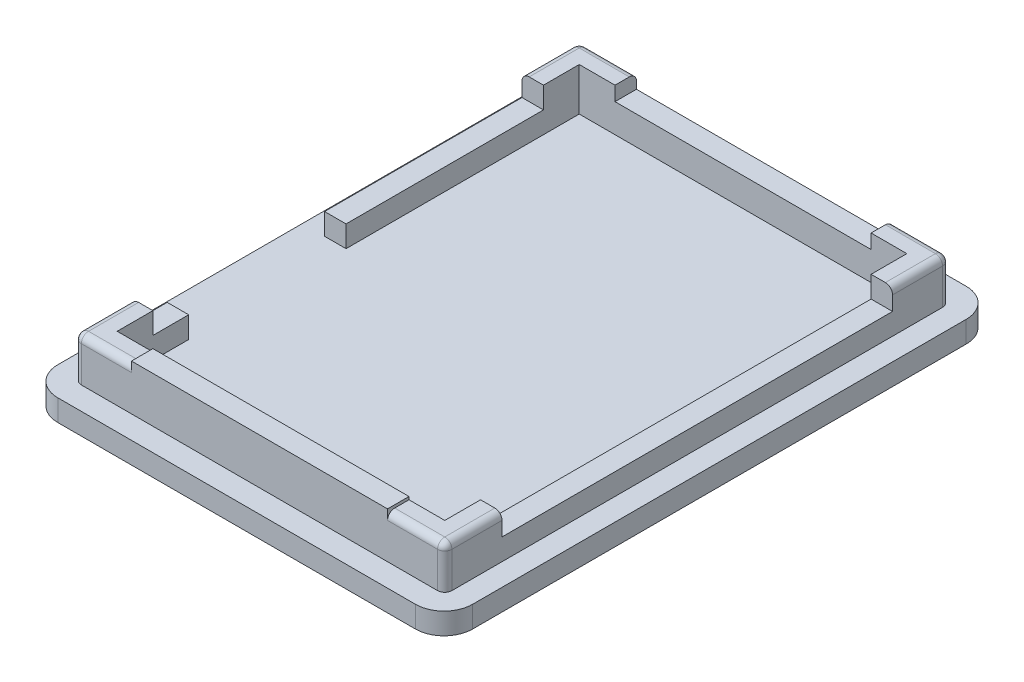
SolidWorks part; units mm, degrees
ref_plane "前视基准面" through (0, 0, 0) normal (0, 0, 1) x (1, 0, 0)
ref_plane "上视基准面" through (0, 0, 0) normal (0, 1, 0) x (1, 0, 0)
ref_plane "右视基准面" through (0, 0, 0) normal (1, 0, 0) x (0, 0, -1)
sketch "草图1" plane through (0, 0, 0) normal (0, 1, 0) x (1, 0, 0)
  line L1 (0, 0) -> (29, 0)
  line L2 (0, 0) -> (0, -38.5)
  line L3 (0, -38.5) -> (29, -38.5)
  line L4 (29, 0) -> (29, -38.5)
extrude "凸台-拉伸2" add sketch "草图1" along normal blind 4.5
sketch "草图3" plane through (0, 4.5, 0) normal (0, 1, 0) x (1, 0, 0)
  line L1 (0, 0) -> (29, 0)
  line L2 (0, 0) -> (0, -38.5)
  line L3 (0, -38.5) -> (29, -38.5)
  line L4 (29, 0) -> (29, -38.5)
  line L5 (1.55, -1.6) -> (27.45, -1.6)
  line L6 (1.55, -1.6) -> (1.55, -36.9)
  line L7 (1.55, -36.9) -> (27.45, -36.9)
  line L8 (27.45, -1.6) -> (27.45, -36.9)
  dimension "D1" = 1.6
  dimension "D2" = 1.55
  dimension "D3" = 1.6
  dimension "D4" = 1.55
extrude "切除-拉伸1" cut sketch "草图3" against normal blind 3
sketch "草图4" plane through (0, 4.5, 0) normal (0, 1, 0) x (1, 0, 0)
  line L0 (27.45, -1.6) -> (1.55, -1.6) construction
  line L1 (3.05, -3.1) -> (25.95, -3.1)
  line L2 (3.05, -3.1) -> (3.05, -35.4)
  line L3 (3.05, -35.4) -> (25.95, -35.4)
  line L4 (25.95, -3.1) -> (25.95, -35.4)
  line L5 (1.55, -1.6) -> (1.55, -36.9) construction
  line L6 (27.45, -36.9) -> (27.45, -1.6) construction
  line L7 (1.55, -36.9) -> (27.45, -36.9) construction
  dimension "D1" = 1.5
  dimension "D2" = 1.5
  dimension "D3" = 1.5
  dimension "D4" = 1.5
extrude "切除-拉伸2" cut sketch "草图4" against normal blind 3
sketch "草图5" plane through (0, 4.5, 0) normal (0, 1, 0) x (1, 0, 0)
  line L0 (27.45, -1.6) -> (1.55, -1.6) construction
  line L1 (5.55, -1.6) -> (23.45, -1.6)
  line L2 (5.55, -1.6) -> (5.55, -3.1)
  line L3 (5.55, -3.1) -> (23.45, -3.1)
  line L4 (23.45, -1.6) -> (23.45, -3.1)
  line L5 (25.95, -3.1) -> (3.05, -3.1) construction
  line L6 (1.55, -1.6) -> (1.55, -36.9) construction
  line L7 (27.45, -36.9) -> (27.45, -1.6) construction
  point P8 (5.55, -2.35)
  point P11 (23.45, -2.35)
  dimension "D1" = 4
  dimension "D2" = 4
extrude "切除-拉伸3" cut sketch "草图5" against normal blind 1
sketch "草图6" plane through (0, 4.5, 0) normal (0, 1, 0) x (1, 0, 0)
  line L0 (1.55, -1.6) -> (1.55, -36.9) construction
  line L1 (1.55, -32.9) -> (3.05, -32.9)
  line L2 (1.55, -32.9) -> (1.55, -5.6)
  line L3 (1.55, -5.6) -> (3.05, -5.6)
  line L4 (3.05, -32.9) -> (3.05, -5.6)
  line L5 (3.05, -3.1) -> (3.05, -35.4) construction
  line L6 (1.55, -36.9) -> (27.45, -36.9) construction
  line L7 (5.55, -1.6) -> (1.55, -1.6) construction
  line L8 (25.95, -35.4) -> (25.95, -3.1) construction
  line L9 (25.95, -32.9) -> (27.45, -32.9)
  line L10 (25.95, -32.9) -> (25.95, -5.6)
  line L11 (25.95, -5.6) -> (27.45, -5.6)
  line L12 (27.45, -32.9) -> (27.45, -5.6)
  line L13 (27.45, -36.9) -> (27.45, -1.6) construction
  line L14 (27.45, -1.6) -> (23.45, -1.6) construction
  point P10 (2.3, -32.9)
  dimension "D1" = 4
  dimension "D2" = 4
  dimension "D3" = 4
  dimension "D4" = 4
extrude "切除-拉伸5" cut sketch "草图6" against normal blind 1.5
fillet "圆角1" radius 2 4 edges at (29, 0.75, 38.5) (0, 0.75, 38.5) (0, 0.75, 0) (29, 0.75, 0)
sketch "草图8" plane through (0, 4.5, 0) normal (0, 1, 0) x (1, 0, 0)
  line L0 (1.55, -36.9) -> (27.45, -36.9) construction
  line L1 (23.45, -36.9) -> (5.55, -36.9)
  line L2 (23.45, -36.9) -> (23.45, -35.4)
  line L3 (23.45, -35.4) -> (5.55, -35.4)
  line L4 (5.55, -36.9) -> (5.55, -35.4)
  line L5 (3.05, -35.4) -> (25.95, -35.4) construction
  line L6 (27.45, -36.9) -> (27.45, -32.9) construction
  line L7 (1.55, -32.9) -> (1.55, -36.9) construction
  dimension "D1" = 4
  dimension "D2" = 4
fillet "圆角5" radius 0.5 4 edges at (27.45, 3, 1.6) (1.55, 3, 1.6) (1.55, 3, 36.9) (27.45, 3, 36.9)
extrude "凸台-拉伸7" add sketch "草图8" along normal blind 0.2
fillet "圆角6" radius 0.5 12 edges at (3.8, 4.5, 1.6) (1.6964, 4.5, 1.7464) (25.2, 4.5, 1.6) (27.3036, 4.5, 1.7464) (25.2, 4.5, 36.9) (27.3036, 4.5, 36.7536) (3.8, 4.5, 36.9) (1.6964, 4.5, 36.7536) (1.55, 4.5, 3.85) (27.45, 4.5, 3.85) (27.45, 4.5, 34.65) (1.55, 4.5, 34.65)
sketch "草图9" plane through (0, 3, 0) normal (0, 1, 0) x (1, 0, 0)
  line L0 (27.45, -32.9) -> (27.45, -5.6) construction
  line L1 (27.45, -28.0181) -> (25.9, -28.0181)
  line L2 (27.45, -28.0181) -> (27.45, -3.3325)
  line L3 (27.45, -3.3325) -> (25.9, -3.3325)
  line L4 (25.9, -28.0181) -> (25.9, -3.3325)
sketch "草图10" plane through (0, 3, 0) normal (0, 1, 0) x (1, 0, 0)
  line L0 (3.05, -32.9) -> (3.05, -5.6) construction
  line L1 (3.05, -19.4) -> (1.55, -19.4)
  line L2 (3.05, -19.4) -> (3.05, -30.4)
  line L3 (3.05, -30.4) -> (1.55, -30.4)
  line L4 (1.55, -19.4) -> (1.55, -30.4)
  line L5 (1.55, -5.6) -> (1.55, -32.9) construction
  line L8 (5.55, -36.9) -> (2.05, -36.9) construction
  point P8 (2.3, -30.4)
  point P11 (2.3, -19.4)
  dimension "D1" = 6.5
  dimension "D2" = 17.5
  dimension "D3" = 11
extrude "切除-拉伸6" cut sketch "草图10" against normal blind 1.5
